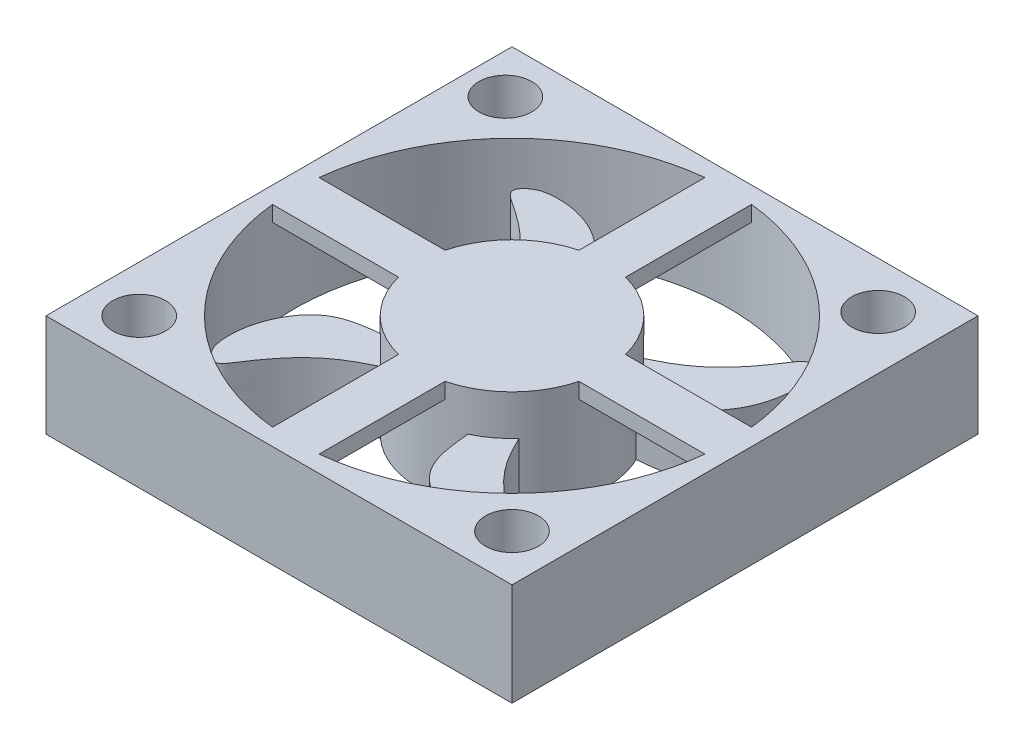
SolidWorks part; units mm, degrees
ref_plane "Front Plane" through (0, 0, 0) normal (0, 0, 1) x (1, 0, 0)
ref_plane "Top Plane" through (0, 0, 0) normal (0, 1, 0) x (1, 0, 0)
ref_plane "Right Plane" through (0, 0, 0) normal (1, 0, 0) x (0, 0, -1)
sketch "Sketch1" plane through (0, 0, 0) normal (0, 1, 0) x (1, 0, 0)
  line L1 (0, 0) -> (30, 0)
  line L2 (0, 0) -> (0, 30)
  line L3 (0, 30) -> (30, 30)
  line L4 (30, 0) -> (30, 30)
  circle A0 centre (15, 15) radius 14
  circle A1 centre (15, 15) radius 6
  dimension "D5" = 28
  dimension "D6" = 12
  dimension "D1" = 30
  dimension "D2" = 30
  dimension "D3" = 15
  dimension "D4" = 15
extrude "Boss-Extrude1" add sketch "Sketch1" along normal blind 6.6 contours A1 | L1 L4 L3 L2 A0
sketch "Sketch2" plane through (0, 6.6, 0) normal (0, 1, 0) x (1, 0, 0)
  line L0 (0, 0) -> (0, 30) construction
  line L2 (13.5, 28.9194) -> (13.5, 20.8095)
  line L4 (16.5, 28.9194) -> (16.5, 20.8095)
  line L6 (1.0806, 16.5) -> (9.1905, 16.5)
  line L8 (1.0806, 13.5) -> (9.1905, 13.5)
  line L10 (0, 0) -> (30, 0) construction
  line L11 (16.5, 9.1905) -> (16.5, 1.0806)
  line L12 (13.5, 9.1905) -> (13.5, 1.0806)
  line L13 (20.8095, 16.5) -> (28.9194, 16.5)
  line L14 (20.8095, 13.5) -> (28.9194, 13.5)
  arc A0 (9.1905, 16.5) -> (9.1905, 13.5) centre (15, 15) ccw
  arc A1 (1.0806, 16.5) -> (1.0806, 13.5) centre (15, 15) ccw
  arc A2 (16.5, 20.8095) -> (13.5, 20.8095) centre (15, 15) ccw
  arc A3 (16.5, 28.9194) -> (13.5, 28.9194) centre (15, 15) ccw
  arc A4 (28.9194, 13.5) -> (28.9194, 16.5) centre (15, 15) ccw
  arc A5 (13.5, 1.0806) -> (16.5, 1.0806) centre (15, 15) ccw
  arc A6 (13.5, 9.1905) -> (16.5, 9.1905) centre (15, 15) ccw
  arc A7 (20.8095, 13.5) -> (20.8095, 16.5) centre (15, 15) ccw
  dimension "D2" = 13.5
  dimension "D4" = 13.5
extrude "Boss-Extrude2" add sketch "Sketch2" against normal blind 1
sketch "Sketch3" plane through (0, 0, 0) normal (0, -1, 0) x (1, 0, 0)
  arc A0 (10.9846, -10.5417) -> (9.5846, -12.4168) centre (15, -15) ccw
  arc A1 (19.4583, -10.9846) -> (17.5832, -9.5846) centre (15, -15) ccw
  arc A2 (19.0154, -19.4583) -> (20.4154, -17.5832) centre (15, -15) ccw
  arc A3 (10.5417, -19.0154) -> (12.4168, -20.4154) centre (15, -15) ccw
  spline S0 degree 3 poles (9.5846, -12.4168) (8.4108, -12.3094) (5.3807, -12.0321) (4.1038, -8.1854) (4.5695, -6.0583) (5.3874, -4.9384) (7.8347, -8.9871) (9.5075, -9.8127) (10.9846, -10.5417) knots 0 0 0 0 0.170032 0.438946 0.451594 0.51455 0.557853 0.884626 0.884626 0.884626 0.884626
  spline S1 degree 3 poles (17.5832, -9.5846) (17.6906, -8.4108) (17.9679, -5.3807) (21.8146, -4.1038) (23.9417, -4.5695) (25.0616, -5.3874) (21.0129, -7.8347) (20.1873, -9.5075) (19.4583, -10.9846) knots 0 0 0 0 0.170032 0.438946 0.451594 0.51455 0.557853 0.884626 0.884626 0.884626 0.884626
  spline S2 degree 3 poles (20.4154, -17.5832) (21.5892, -17.6906) (24.6193, -17.9679) (25.8962, -21.8146) (25.4305, -23.9417) (24.6126, -25.0616) (22.1653, -21.0129) (20.4925, -20.1873) (19.0154, -19.4583) knots 0 0 0 0 0.170032 0.438946 0.451594 0.51455 0.557853 0.884626 0.884626 0.884626 0.884626
  spline S3 degree 3 poles (12.4168, -20.4154) (12.3094, -21.5892) (12.0321, -24.6193) (8.1854, -25.8962) (6.0583, -25.4305) (4.9384, -24.6126) (8.9871, -22.1653) (9.8127, -20.4925) (10.5417, -19.0154) knots 0 0 0 0 0.170032 0.438946 0.451594 0.51455 0.557853 0.884626 0.884626 0.884626 0.884626
  point P29 (15, -15)
  dimension "D1" = 4
extrude "Boss-Extrude3" add sketch "Sketch3" against normal blind 4
sketch "Sketch4" plane through (0, 6.6, 0) normal (0, 1, 0) x (1, 0, 0)
  line L0 (0, 0) -> (0, 30) construction
  line L1 (0, 0) -> (30, 0) construction
  circle A0 centre (2.5712, 27) radius 1.7
  circle A1 centre (26.5712, 27) radius 1.7
  circle A2 centre (27, 3) radius 1.7
  circle A3 centre (3, 3) radius 1.7
  point P10 (26.2142, 1.6945)
  dimension "D5" = 3.4
  dimension "D6" = 3.4
  dimension "D7" = 3.4
  dimension "D8" = 3.4
  dimension "D1" = 24
  dimension "D2" = 24
  dimension "D3" = 24
  dimension "D4" = 24
  dimension "D9" = 3
  dimension "D10" = 3
extrude "Cut-Extrude1" cut sketch "Sketch4" against normal through all
